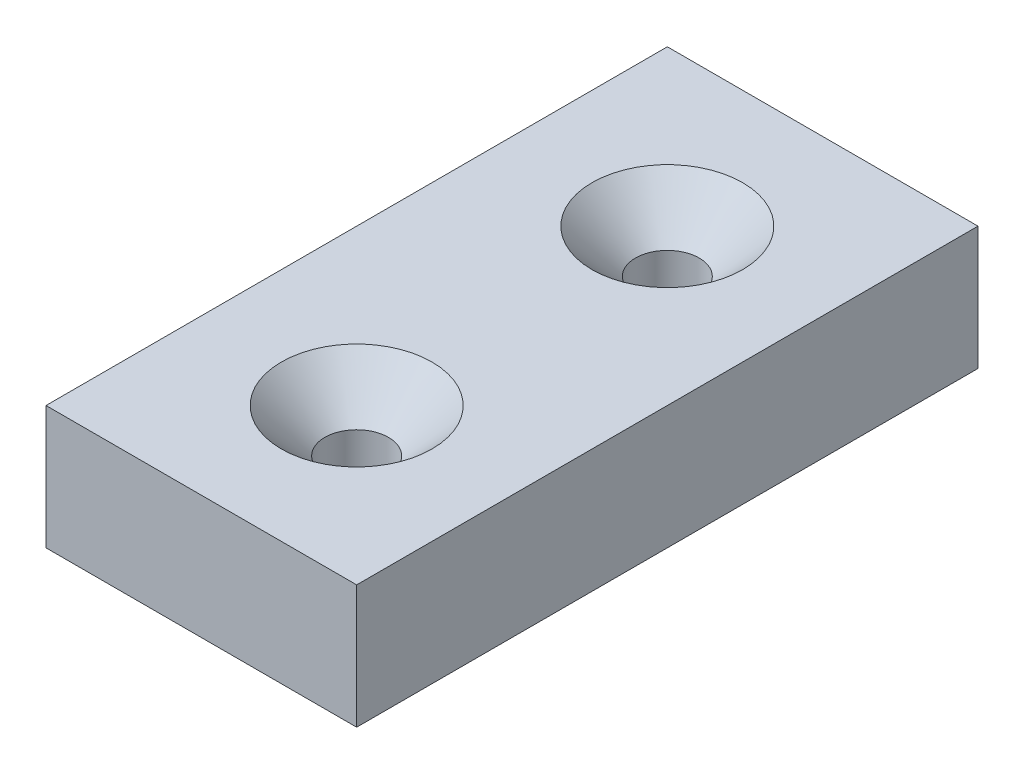
SolidWorks part; units mm, degrees
ref_plane "Top Plane" through (0, 0, 0) normal (0, 0, 1) x (1, 0, 0)
ref_plane "Front Plane" through (0, 0, 0) normal (0, 1, 0) x (1, 0, 0)
ref_plane "Right Plane" through (0, 0, 0) normal (1, 0, 0) x (0, 0, -1)
sketch "Sketch1" plane through (0, -110.0687, 0) normal (0, 1, 0) x (1, 0, 0)
  line L0 (78.3339, -33.4173) -> (78.3339, -91.8373) construction
  line L1 (78.3339, -82.6273) -> (58.3339, -82.6273)
  line L2 (78.3339, -82.6273) -> (78.3339, -42.6273)
  line L3 (78.3339, -42.6273) -> (58.3339, -42.6273)
  line L4 (58.3339, -82.6273) -> (58.3339, -42.6273)
  circle A0 centre (68.3339, -72.6273) radius 2.05
  circle A1 centre (68.3339, -52.6273) radius 2.05
  circle A2 centre (68.3339, -72.6273) radius 2.05 construction
  circle A3 centre (68.3339, -52.6273) radius 2.05 construction
  point P6 (78.3339, -62.6273)
  point P7 (78.3339, -62.6273)
  point P20 (68.3339, -82.6273)
  point P28 (76.2592, -63.0201)
  point P30 (77.6466, -62.8929)
  point P31 (77.547, -62.986)
  point P32 (0, 0)
  point P33 (0, 0)
  point P34 (0, 0)
  point P35 (0, 0)
  point P36 (0, 0)
  point P37 (0, 0)
  point P38 (0, 0)
  point P39 (0, 0)
  point P40 (0, 0)
  point P41 (77.7539, -53.9799)
  dimension "D2" = 4.1
  dimension "D3" = 10
extrude "Boss-Extrude1" add sketch "Sketch1" along normal blind 7.9375
chamfer "Chamfer1" distance 2.8 angle 45 2 edges at (68.3339, -102.1312, 74.6773) (68.3339, -102.1312, 54.6773)
